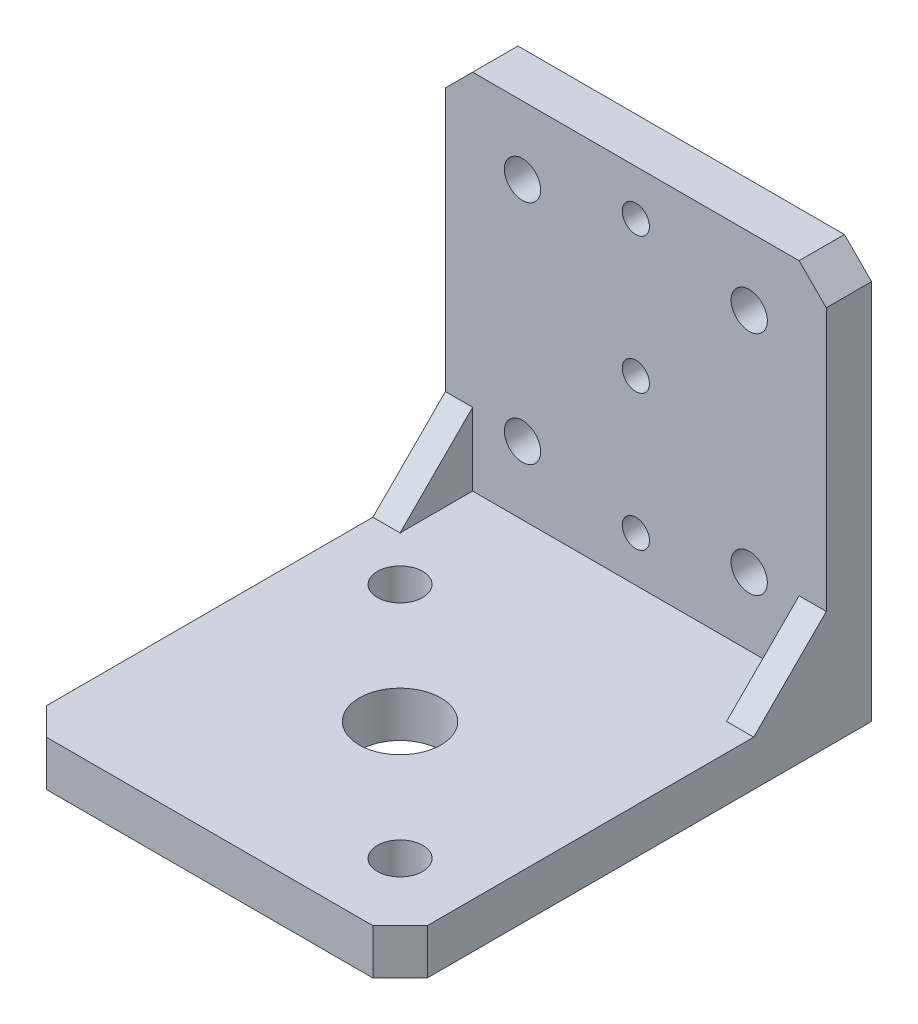
SolidWorks part; units mm, degrees
ref_plane "Front Plane" through (0, 0, 0) normal (0, 0, 1) x (1, 0, 0)
ref_plane "Top Plane" through (0, 0, 0) normal (0, 1, 0) x (1, 0, 0)
ref_plane "Right Plane" through (0, 0, 0) normal (1, 0, 0) x (0, 0, -1)
sketch "Sketch1" plane through (0, 0, 0) normal (0, 1, 0) x (1, 0, 0)
  line L1 (-21, -23.5) -> (21, -23.5)
  line L2 (-21, -23.5) -> (-21, 23.5)
  line L3 (-21, 23.5) -> (21, 23.5)
  line L4 (21, -23.5) -> (21, 23.5)
  line L5 (-21, -23.5) -> (21, 23.5) construction
  line L6 (-21, 23.5) -> (21, -23.5) construction
  point P0 (0, 0)
  dimension "D1" = 47
  dimension "D2" = 42
extrude "Boss-Extrude1" add sketch "Sketch1" along normal blind 5
sketch "Sketch2" plane through (0, 5, 0) normal (0, 1, 0) x (1, 0, 0)
  line L0 (-13.0815, 10.5815) -> (13.0815, -15.5815) construction
  line L1 (-21, 23.5) -> (-21, -23.5) construction
  line L2 (0, 23.5) -> (0, -23.5) construction
  line L3 (21, 23.5) -> (-21, 23.5) construction
  line L4 (-21, -23.5) -> (21, -23.5) construction
  circle A0 centre (-13.0815, 10.5815) radius 2.5
  circle A1 centre (13.0815, -15.5815) radius 2.5
  circle A2 centre (0, -2.5) radius 4.5
  point P3 (0, -2.5)
  dimension "D2" = 45
  dimension "D3" = 5
  dimension "D4" = 9
  dimension "D1" = 37
  dimension "D5" = 21
sketch "Sketch4" plane through (0, 0, -23.5) normal (0, 0, -1) x (-1, 0, 0)
  line L0 (21, 5) -> (21, 0) construction
  line L1 (-21, 0) -> (21, 0)
  line L2 (-21, 0) -> (-21, 45)
  line L3 (-21, 45) -> (21, 45)
  line L4 (21, 0) -> (21, 45)
  line L5 (-21, 5) -> (21, 5) construction
  dimension "D1" = 40
extrude "Boss-Extrude2" add sketch "Sketch4" along normal blind 5
sketch "Sketch5" plane through (21, 0, 0) normal (1, 0, 0) x (0, 0, -1)
  line L0 (23.5, 13) -> (15.5, 5)
  line L1 (23.5, 45) -> (23.5, 5) construction
  line L2 (-23.5, 5) -> (23.5, 5) construction
  line L3 (15.5, 5) -> (23.5, 5)
  line L4 (23.5, 5) -> (23.5, 13)
  dimension "D1" = 8
extrude "Boss-Extrude3" add sketch "Sketch5" against normal blind 3
sketch "Sketch6" plane through (-21, 0, 0) normal (-1, 0, 0) x (0, 0, 1)
  line L0 (-23.5, 13) -> (-15.5, 5)
  line L1 (-23.5, 5) -> (-23.5, 45) construction
  line L2 (-23.5, 5) -> (23.5, 5) construction
  line L3 (-15.5, 5) -> (-23.5, 5)
  line L4 (-23.5, 5) -> (-23.5, 13)
  dimension "D1" = 8
extrude "Boss-Extrude4" add sketch "Sketch6" against normal blind 3
extrude "Cut-Extrude1" cut sketch "Sketch2" against normal through all
sketch "Sketch9" plane through (0, 0, -23.5) normal (0, 0, 1) x (1, 0, 0)
  line L0 (0, 45) -> (0, 5) construction
  line L1 (-21, 45) -> (21, 45) construction
  line L2 (18, 5) -> (-18, 5) construction
  line L4 (-12.5, 12.5) -> (12.5, 12.5) construction
  line L5 (-12.5, 12.5) -> (-12.5, 37.5) construction
  line L6 (-12.5, 37.5) -> (12.5, 37.5) construction
  line L7 (12.5, 12.5) -> (12.5, 37.5) construction
  line L8 (-12.5, 12.5) -> (12.5, 37.5) construction
  line L9 (-12.5, 37.5) -> (12.5, 12.5) construction
  circle A0 centre (-12.5, 37.5) radius 2
  circle A1 centre (12.5, 37.5) radius 2
  circle A2 centre (12.5, 12.5) radius 2
  circle A3 centre (-12.5, 12.5) radius 2
  point P6 (0, 25)
  dimension "D1" = 4
  dimension "D2" = 25
  dimension "D3" = 25
extrude "Cut-Extrude4" cut sketch "Sketch9" against normal through all
chamfer "Chamfer2" distance 3 angle 45 4 edges at (-21, 2.5, 23.5) (21, 2.5, 23.5) (21, 45, -26) (-21, 45, -26)
sketch "Sketch10" plane through (0, 0, -28.5) normal (0, 0, -1) x (-1, 0, 0)
  circle A0 centre (0, 25) radius 1.5 construction
  circle A1 centre (0, 25) radius 1.5
  circle A2 centre (0, 10) radius 1.5 construction
  circle A3 centre (0, 10) radius 1.5
  circle A4 centre (0, 40) radius 1.5 construction
  circle A5 centre (0, 40) radius 1.5
extrude "Cut-Extrude5" cut sketch "Sketch10" against normal up to next
